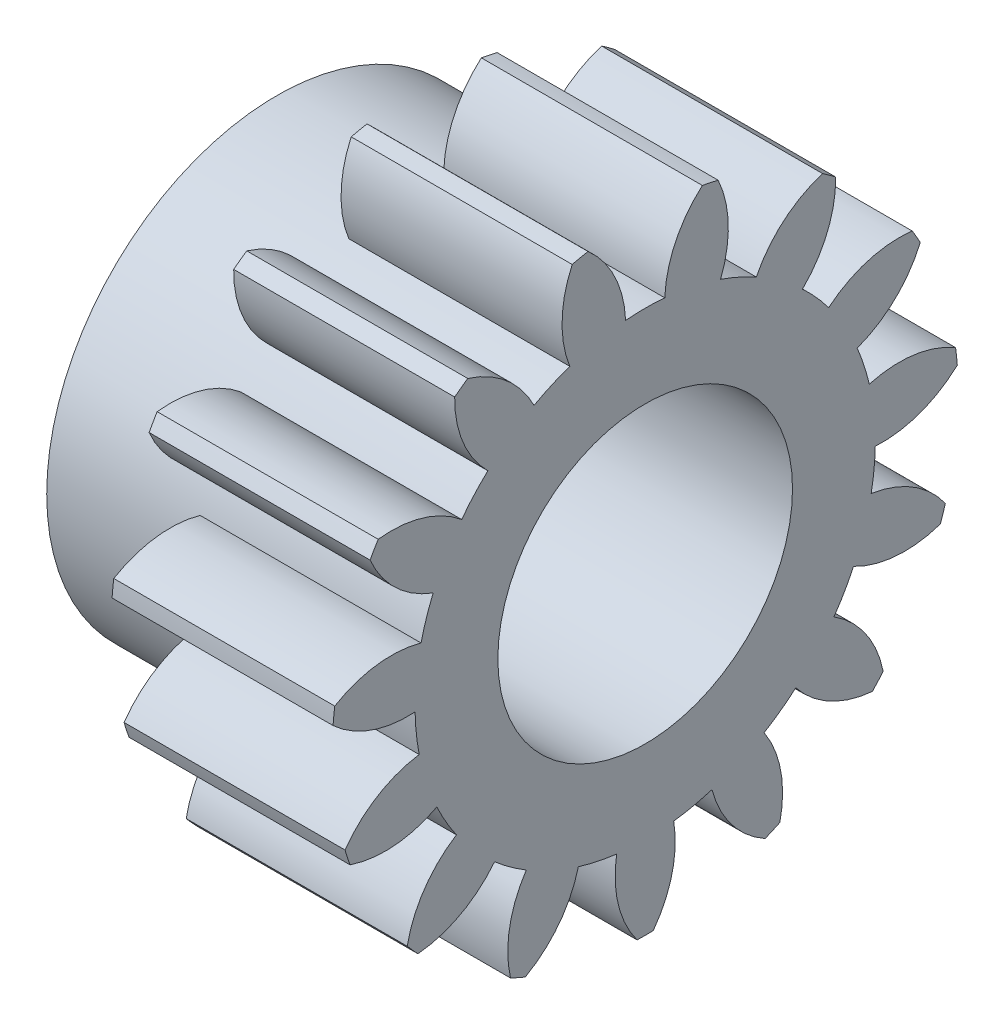
SolidWorks part; units mm, degrees
ref_plane "Plane1" through (0, 0, 0) normal (0, 0, 1) x (1, 0, 0)
ref_plane "Plane2" through (0, 0, 0) normal (0, 1, 0) x (1, 0, 0)
ref_plane "Plane3" through (0, 0, 0) normal (1, 0, 0) x (0, 0, -1)
sketch "HoldingSke" plane through (0, 0, 0) normal (0, 1, 0) x (1, 0, 0)
  line L0 (0, 0) -> (1.9319, -0.5176)
  line L1 (-15, 0) -> (100, 0) construction
  line L2 (0, 0) -> (-2.1039, 2.3779)
  line L3 (0, 0) -> (-11.863, 4.5341)
  line L4 (0, 0) -> (8.3417, 2.2352)
  line L5 (0, 0) -> (-4.6848, -1.7473)
  line L6 (0, 0) -> (-2.4869, -1.6779)
  line L7 (-2.1039, 2.3779) -> (-1.0276, 7.2607)
  line L8 (-76.2, 54.61) -> (-75.5, 54.61)
  line L9 (-71.009, 38.7566) -> (-53.1078, 45.2721)
  line L10 (-76.2, 71.12) -> (104.1128, 71.12)
  line L11 (0, 0) -> (-3, 0)
  line L12 (-76.2, 101.6) -> (-76.181, 101.6)
  line L13 (24.9733, 27.94) -> (52.9518, 28.4284)
  line L14 (24.9733, 27.94) -> (24.9743, 27.94)
  line L15 (24.9733, 27.94) -> (100.4006, 29.5858)
  line L16 (-63.627, -0.5) -> (-12.827, -0.5)
  circle A0 centre (0, 0) radius 2
  circle A1 centre (0, 0) radius 3.124
  circle A2 centre (0, 0) radius 5
  circle A3 centre (0, 0) radius 2
  dimension "MHD" = 6.248
  dimension "Hub_dia" = 10
  dimension "Bore" = 4
  dimension "MBD" = 4
  dimension "Num_teeth" = 15
  dimension "Pitch" = 2
  dimension "Overall_len" = 5
  dimension "Show_teeth" = 15
  dimension "Thickness" = 3
  dimension "OAL" = 5.0001
  dimension "T_dim" = 0.7
  dimension "Ap" = 20
  dimension "H" = 19.05
  dimension "Pitch_radius" = 180.3128
  dimension "Width" = 3
  dimension "Backlash" = 0.019
  dimension "Addendum_fac" = 1
  dimension "Dedendum_fac" = 1.25
  dimension "Clearance_fac" = 0.25
  dimension "Dedendum_add" = 0.001
  dimension "Module" = 0.5
sketch "BasProSke" plane through (0, 0, 0) normal (0, 1, 0) x (1, 0, 0)
  line L0 (-10, 0) -> (60, 0) construction
  line L1 (0, 0) -> (0, 4.25)
  line L2 (0, 0) -> (3, 0)
  line L3 (3, 0) -> (3, 4.25)
  line L4 (3, 4.25) -> (0, 4.25)
  dimension "Thickness" = 3
  dimension "Diameter" = 8.5
revolve "Base-Revolve" add sketch "BasProSke" angle 360 about L0
sketch "TooCutSke" plane through (0, 0, 0) normal (1, 0, 0) x (0, 0, -1)
  line L1 (0, 0) -> (0, 107) construction
  line L2 (0, 0) -> (-0.4252, 3.7258) construction
  line L3 (0, 0) -> (-1.5522, 7.3025) construction
  line L4 (-0.4252, 3.7258) -> (-0.7761, 3.6512) construction
  arc A0 (0.2658, 3.1127) -> (-0.2658, 3.1127) centre (0, 0) ccw
  arc A1 (0.8008, 4.1997) -> (-0.8008, 4.1997) centre (0, 0) ccw
  circle A2 centre (0, 0) radius 3.75 construction
  circle A3 centre (0, 0) radius 3.5238 construction
  arc A4 (-0.2658, 3.1127) -> (-0.8008, 4.1997) centre (-1.7645, 3.0503) ccw
  arc A5 (0.8008, 4.1997) -> (0.2658, 3.1127) centre (1.7645, 3.0503) ccw
  dimension "Root_dia" = 6.248
  dimension "Overcut_dia" = 8.5508
  dimension "Pitch_dia" = 7.5
  dimension "Base_dia" = 7.0477
  dimension "Flank_rad" = 1.5
  dimension "Half_ang" = 12
  dimension "Half_CT" = 0.3587
extrude "ToothCut" cut sketch "TooCutSke" along normal through all
fillet "Breaks" [suppressed] radius 0.01
fillet "RootFillets" [suppressed] radius 0.126
pattern_circular "TeethCuts" count 15 every 24 about axis through (-10, 0, 0) along (1, 0, 0) of "ToothCut", "RootFillets", "Breaks"
sketch "HubNeaOneSke" plane through (0, 0, 0) normal (-1, 0, 0) x (0, 0, 1)
  circle A0 centre (0, 0) radius 3.124
  dimension "Diameter" = 6.248
extrude "HubNearOne" add sketch "HubNeaOneSke" along normal blind 2.0001
sketch "HubNeaBotSke" plane through (0, 0, 0) normal (-1, 0, 0) x (0, 0, 1)
  circle A0 centre (0, 0) radius 3.124
  dimension "Diameter" = 6.248
extrude "HubNearBoth" [suppressed] add sketch "HubNeaBotSke" along normal blind 1
ref_plane "FarPln" through (3, 0, 0) normal (1, 0, 0) x (0, 0, -1)
sketch "HubFarSke" plane through (3, 0, 0) normal (1, 0, 0) x (0, 0, -1)
  circle A0 centre (0, 0) radius 3.124
  dimension "Diameter" = 6.248
extrude "HubFar" [suppressed] add sketch "HubFarSke" along normal blind 1
sketch "BorSke" plane through (0, 0, 0) normal (1, 0, 0) x (0, 0, -1)
  circle A0 centre (0, 0) radius 2
  dimension "Diameter" = 4
extrude "Bore" cut sketch "BorSke" along normal mid plane 10.0001
sketch "KeySke" plane through (0, 0, 0) normal (1, 0, 0) x (0, 0, -1)
  line L0 (-0.8, 0) -> (-0.8, 2.7)
  line L1 (-0.8, 2.7) -> (0.8, 2.7)
  line L2 (0.8, 2.7) -> (0.8, 0)
  line L3 (0, 0) -> (0, 34) construction
  line L4 (-0.8, 0) -> (0.8, 0)
  dimension "Offset" = 2.7
  dimension "Width" = 1.6
extrude "Keyway" [suppressed] cut sketch "KeySke" along normal mid plane 10.0001
pattern_circular "Keyway2" [suppressed] count 2 every 90 about axis through (-10, 0, 0) along (1, 0, 0)
equation "' \"Module@HoldingSke\" = 6.35"
equation "' \"Num_teeth@HoldingSke\" = 12"
equation "' \"Ap@HoldingSke\" =  20"
equation "' \"Ap@HoldingSke\" = 20"
equation "' \"Width@HoldingSke\" = 0.5 * 25.4"
equation "' \"Hub_dia@HoldingSke\"= 1 * 25.4"
equation "' \"Hub_dia@HoldingSke\" = 1 * 25.4"
equation "' \"Overall_len@HoldingSke\" = 1.0 * 25.4"
equation "' \"Bore@HoldingSke\" = 0.75 * 25.4"
equation "' \"T_dim@HoldingSke\" = 0.1 * 25.4"
equation "' \"Width@KeySke\" = 0.25 * 25.4"
equation "' \"Show_teeth@HoldingSke\" = 13"
equation "' \"Backlash@HoldingSke\" = 0.009 * 25.4"
equation "' \"Addendum_fac@HoldingSke\" = 1.0"
equation "' \"Dedendum_fac@HoldingSke\" = 1.25"
equation "' \"Dedendum_add@HoldingSke\" = 0.00005 * 25.4"
equation "' \"Clearance_fac@HoldingSke\" = 0.25"
equation "\"Pitch@HoldingSke\" = 1 / \"Module@HoldingSke\""
equation "\"Overcut_dia@TooCutSke\" = (\"Num_teeth@HoldingSke\" + 2 * \"Addendum_fac@HoldingSke\") / \"Pitch@HoldingSke\" + 0.002 * 25.4"
equation "\"Pitch_dia@TooCutSke\" = \"Num_teeth@HoldingSke\" / \"Pitch@HoldingSke\""
equation "\"Base_dia@TooCutSke\" = \"Num_teeth@HoldingSke\" / \"Pitch@HoldingSke\" * cos((\"Ap@HoldingSke\"  * 3.14159265 / 180))"
equation "\"Root_dia@TooCutSke\" = (\"Num_teeth@HoldingSke\" + 2) / \"Pitch@HoldingSke\" - 2 * (\"Addendum_fac@HoldingSke\" + \"Dedendum_fac@HoldingSke\") / \"Pitch@HoldingSke\" - \"Dedendum_add@HoldingSke\" * 2"
equation "\"Half_ang@TooCutSke\" = 180 / \"Num_teeth@HoldingSke\""
equation "\"Half_CT@TooCutSke\" = \"Num_teeth@HoldingSke\" / \"Pitch@HoldingSke\" * sin((3.14159265 / 2 / \"Num_teeth@HoldingSke\")) / 2 - 7 * \"Backlash@HoldingSke\" / 4"
equation "\"Flank_rad@TooCutSke\" = \"Num_teeth@HoldingSke\" / \"Pitch@HoldingSke\" / 5"
equation "\"Radius@RootFillets\" = \"Clearance_fac@HoldingSke\" / \"Pitch@HoldingSke\" + \"Dedendum_add@HoldingSke\""
equation "\"Break_rad@Breaks\" = 0.02 / \"Pitch@HoldingSke\""
equation "\"Thickness@HoldingSke\" = \"Width@HoldingSke\""
equation "\"OAL@HoldingSke\" = \"Thickness@HoldingSke\""
equation "\"MHD@HoldingSke\" = (\"Num_teeth@HoldingSke\" + 2) / \"Pitch@HoldingSke\" - 2 * (\"Addendum_fac@HoldingSke\" + \"Dedendum_fac@HoldingSke\")  / \"Pitch@HoldingSke\" - \"Dedendum_add@HoldingSke\" * 2"
equation "\"MBD@HoldingSke\" = (\"Num_teeth@HoldingSke\" + 2) / \"Pitch@HoldingSke\" - 2 * (\"Addendum_fac@HoldingSke\" + \"Dedendum_fac@HoldingSke\")  / \"Pitch@HoldingSke\" - \"Dedendum_add@HoldingSke\" * 2 - 0.002 * 25.4"
equation "\"MHD@HoldingSke\" = ((sgn( \"MHD@HoldingSke\" - \"Hub_dia@HoldingSke\" )-1)*( \"MHD@HoldingSke\" - \"Hub_dia@HoldingSke\" ))/-2+ \"Hub_dia@HoldingSke\""
equation "\"MBD@HoldingSke\" = ((sgn( \"MBD@HoldingSke\" - \"Bore@HoldingSke\" )-1)*( \"MBD@HoldingSke\" - \"Bore@HoldingSke\" ))/-2+ \"Bore@HoldingSke\""
equation "\"OAL@HoldingSke\" = ((sgn( \"OAL@HoldingSke\" - \"Overall_len@HoldingSke\" )+1)*( \"OAL@HoldingSke\" - \"Overall_len@HoldingSke\" ))/2 + \"Overall_len@HoldingSke\" + 0.000002 * 25.4"
equation "\"Num_teeth@TeethCuts\" = int( \"Show_teeth@HoldingSke\" ) + 1"
equation "\"Num_teeth@TeethCuts\" = ((sgn( \"Num_teeth@TeethCuts\" - \"Num_teeth@HoldingSke\" )-1)*( \"Num_teeth@TeethCuts\" - \"Num_teeth@HoldingSke\" ))/-2+ \"Num_teeth@HoldingSke\""
equation "\"Num_teeth@TeethCuts\" = ((sgn( \"Num_teeth@TeethCuts\" - 2.0)+1)*( \"Num_teeth@TeethCuts\" - 2.0))/2 +2.0"
equation "\"Angle@TeethCuts\" = 360.0 / \"Num_teeth@HoldingSke\""
equation "\"Diameter@BasProSke\" = (\"Num_teeth@HoldingSke\" + 2 * \"Addendum_fac@HoldingSke\") / \"Pitch@HoldingSke\""
equation "\"Thickness@BasProSke\"  = \"Thickness@HoldingSke\""
equation "' \"Fillet_rad@BasProSke\" =  \"Thickness@HoldingSke\" * 0.05"
equation "' \"Fillet_rad@BasProSke\" = \"Thickness@HoldingSke\" * 0.05"
equation "\"MHD@HoldingSke\" = ((sgn( \"MHD@HoldingSke\" - \"Root_dia@TooCutSke\" )-1)*( \"MHD@HoldingSke\" - \"Root_dia@TooCutSke\" ))/-2+ \"Root_dia@TooCutSke\""
equation "\"Diameter@HubNeaOneSke\" = \"MHD@HoldingSke\""
equation "\"Length@HubNearOne\" = \"OAL@HoldingSke\" - \"Thickness@BasProSke\""
equation "\"Diameter@HubNeaBotSke\" = \"MHD@HoldingSke\""
equation "\"Length@HubNearBoth\" = ( \"OAL@HoldingSke\" - \"Thickness@BasProSke\" ) / 2.0"
equation "\"Thickness@FarPln\" = \"Thickness@BasProSke\""
equation "\"Diameter@HubFarSke\" = \"MHD@HoldingSke\""
equation "\"Length@HubFar\" = ( \"OAL@HoldingSke\" - \"Thickness@BasProSke\" ) / 2.0"
equation "\"Diameter@BorSke\" = \"MBD@HoldingSke\""
equation "\"D1@Bore\" = \"OAL@HoldingSke\" * 2.0"
equation "\"D1@Keyway\" = \"OAL@HoldingSke\" * 2.0"
equation "\"Offset@KeySke\" = \"T_dim@HoldingSke\" + \"MBD@HoldingSke\" / 2.0"
